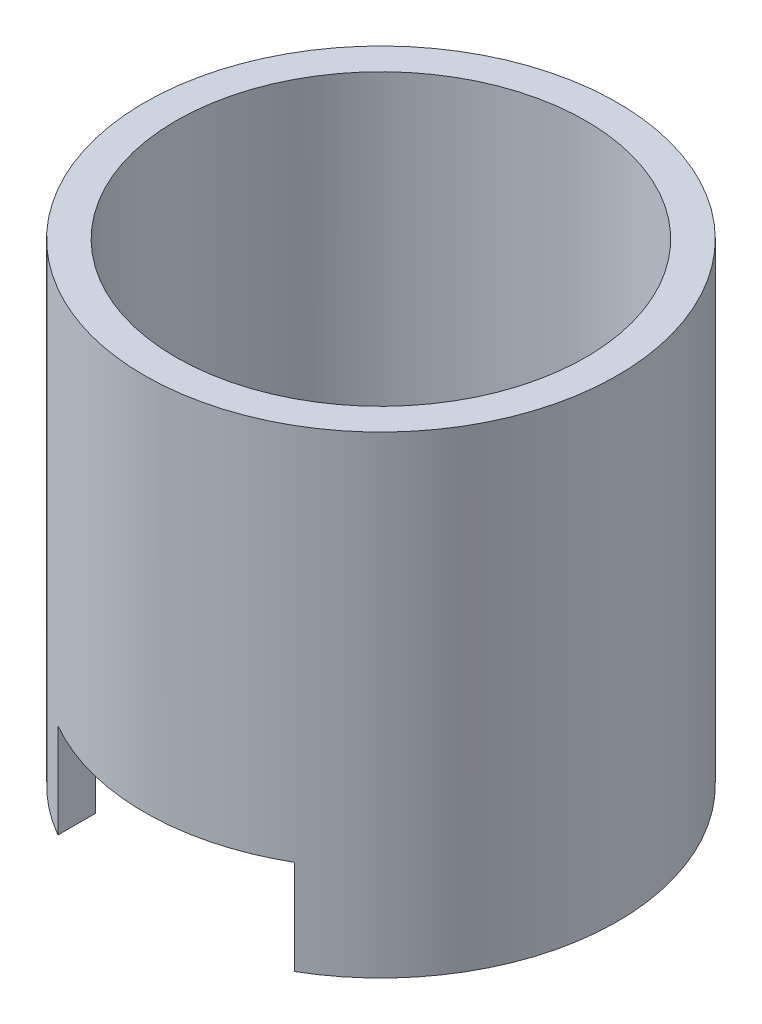
SolidWorks part; units mm, degrees
ref_plane "Ön Düzlem" through (0, 0, 0) normal (0, 0, 1) x (1, 0, 0)
ref_plane "Üst Düzlem" through (0, 0, 0) normal (0, 1, 0) x (1, 0, 0)
ref_plane "Sağ Düzlem" through (0, 0, 0) normal (1, 0, 0) x (0, 0, -1)
sketch "Çizim1" plane through (0, 0, 0) normal (0, 1, 0) x (1, 0, 0)
  circle A0 centre (0, 0) radius 150
  circle A1 centre (0, 0) radius 130
  dimension "D1" = 300
  dimension "D2" = 260
extrude "Yükseklik-Ekstrüzyon1" add sketch "Çizim1" along normal blind 300
sketch "Çizim2" plane through (0, 0, 0) normal (0, 0, 1) x (1, 0, 0)
  line L0 (0, 0) -> (0, 60)
  line L1 (0, 60) -> (75, 60)
  line L2 (0, 60) -> (-75, 60)
  line L3 (-75, 60) -> (-75, 0)
  line L4 (-75, 0) -> (75, 0)
  line L5 (-150, 0) -> (150, 0) construction
  line L6 (75, 0) -> (75, 60)
extrude "Kes-Ekstrüzyon1" cut sketch "Çizim2" along normal blind 180 contours L3 L4 L0 L2 | L4 L6 L1 L0
